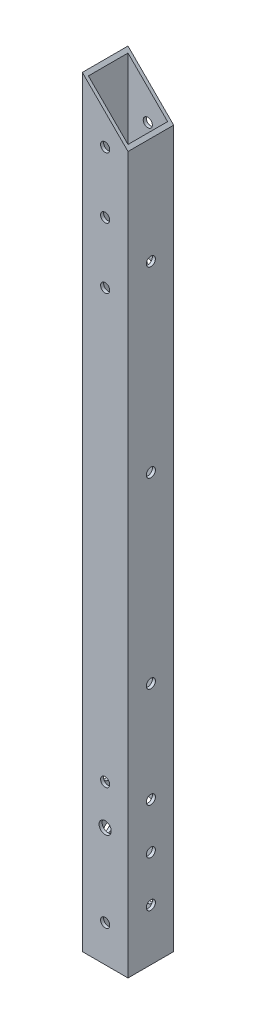
SolidWorks part; units mm, degrees
material "6061-O (SS)"
ref_plane "前视基准面" through (0, 0, 0) normal (0, 0, 1) x (1, 0, 0)
ref_plane "上视基准面" through (0, 0, 0) normal (0, 1, 0) x (1, 0, 0)
ref_plane "右视基准面" through (0, 0, 0) normal (1, 0, 0) x (0, 0, -1)
sketch "草图1" plane through (0, 0, 0) normal (0, 1, 0) x (1, 0, 0)
  line L0 (-6.5, 6.5) -> (6.5, 6.5)
  line L1 (-7.5, -7.5) -> (7.5, -7.5)
  line L2 (-7.5, -7.5) -> (-7.5, 7.5)
  line L3 (-7.5, 7.5) -> (7.5, 7.5)
  line L4 (7.5, -7.5) -> (7.5, 7.5)
  line L5 (-7.5, -7.5) -> (7.5, 7.5) construction
  line L6 (-7.5, 7.5) -> (7.5, -7.5) construction
  line L7 (6.5, -6.5) -> (6.5, 6.5)
  line L8 (-6.5, -6.5) -> (6.5, -6.5)
  line L9 (-6.5, -6.5) -> (-6.5, 6.5)
  point P0 (0, 0)
  dimension "D1" = 15
  dimension "D2" = 1
extrude "凸台-拉伸1" add sketch "草图1" along normal blind 250
sketch "草图2" plane through (0, 0, 7.5) normal (0, 0, 1) x (1, 0, 0)
  line L0 (7.5, 250) -> (7.5, 235)
  line L1 (7.5, 235) -> (-7.5, 250)
  line L2 (-7.5, 250) -> (-7.5, 0) construction
  line L3 (-7.5, 250) -> (7.5, 250)
  line L4 (7.5, 250) -> (7.5, 0) construction
  line L5 (0, 242.5) -> (0, 0) construction
  circle A0 centre (0, 232.5) radius 1.5
  circle A1 centre (0, 212.5) radius 1.5
  circle A2 centre (0, 192.5) radius 1.5
  circle A3 centre (0, 12) radius 1.5
  circle A4 centre (0, 39) radius 2
  circle A5 centre (0, 52) radius 1.5
  dimension "D1" = 20
  dimension "D2" = 20
  dimension "D3" = 10
  dimension "D4" = 3
  dimension "D6" = 4
  dimension "D7" = 27
  dimension "D8" = 13
  dimension "D5" = 12
extrude "切除-拉伸1" cut sketch "草图2" against normal through all
sketch "草图3" plane through (7.5, 0, 0) normal (1, 0, 0) x (0, 0, -1)
  line L0 (0, 0) -> (0, 250) construction
  line L1 (7.5, 250) -> (-7.5, 250) construction
  line L2 (-7.5, 0) -> (7.5, 0) construction
  circle A0 centre (0, 17) radius 1.5
  circle A1 centre (0, 32) radius 1.5
  circle A2 centre (0, 47) radius 1.5
  circle A3 centre (0, 80) radius 1.5
  circle A4 centre (0, 140) radius 1.5
  circle A5 centre (0, 200) radius 1.5
  dimension "D1" = 17
  dimension "D2" = 15
  dimension "D3" = 15
  dimension "D4" = 3
  dimension "D5" = 50
  dimension "D6" = 60
  dimension "D7" = 60
extrude "切除-拉伸2" cut sketch "草图3" against normal through all
